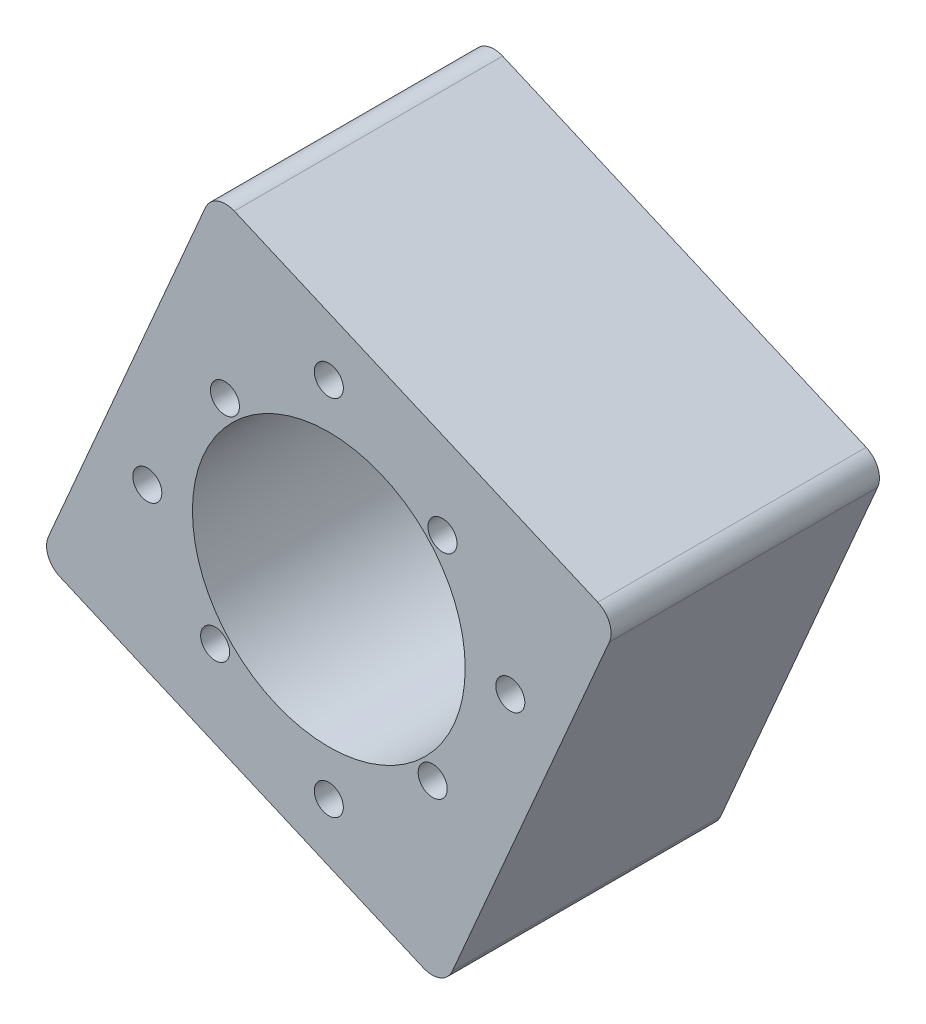
SolidWorks part; units mm, degrees
ref_plane "Plan de face" through (0, 0, 0) normal (0, 0, 1) x (1, 0, 0)
ref_plane "Plan de dessus" through (0, 0, 0) normal (0, 1, 0) x (1, 0, 0)
ref_plane "Plan de droite" through (0, 0, 0) normal (1, 0, 0) x (0, 0, -1)
sketch "Esquisse1" plane through (0, 0, 0) normal (0, 0, 1) x (1, 0, 0)
  circle A0 centre (0, 0) radius 50
  dimension "D1" = 100
extrude "Boss.-Extru.1" add sketch "Esquisse1" along normal blind 61
sketch "Esquisse2" plane through (0, 0, 0) normal (0, 0, -1) x (-1, 0, 0)
  circle A0 centre (0, 0) radius 31
  dimension "D1" = 62
extrude "Enlèv. mat.-Extru.1" cut sketch "Esquisse2" against normal blind 72
sketch "Esquisse8" plane through (0, 0, 0) normal (0, 0, -1) x (-1, 0, 0)
  circle A2 centre (0, 0) radius 41.25
  circle A3 centre (0, 0) radius 41.25 construction
  dimension "D1" = 8.75
hole_wizard "Chambrage pour vis à tête ronde bombée M61" positions "Esquisse12" profile "Esquisse11" counterbore size "M6" standard "Ansi Metric" end condition through all
sketch "Esquisse12" plane through (0, 0, 0) normal (0, 0, -1) x (-1, 0, 0)
  circle A0 centre (0, 0) radius 41.25 construction
  point P0 (41.25, 0)
  point P4 (0, 41.25)
  point P6 (-41.25, 0)
  point P8 (0, -41.25)
sketch "Esquisse11" plane through (-41.25, 0, 0) normal (1, 0, 0) x (0, 1, 0)
  line L0 (0, 0) -> (0, 61)
  line L1 (0, 61) -> (3.3, 61)
  line L3 (3.3, 61) -> (3.3, 4.6)
  line L4 (3.3, 4.6) -> (6.5, 4.6)
  line L5 (6.5, 4.6) -> (6.5, 0)
  line L7 (6.5, 0) -> (0, 0)
  line L11 (0, -6.35) -> (0, 107.95) construction
  dimension "Diamètre du perçage jusqu'au prochain" = 6.6
  dimension "Profondeur du perçage jusqu'au prochain" = 61
  dimension "Diamètre du chambrage" = 13
  dimension "Profondeur du chambrage" = 4.6
hole_wizard "Dégagement M61" positions "Esquisse18" profile "Esquisse19" hole size "M6" standard "JIS"
sketch "Esquisse18" plane through (0, 0, 61) normal (0, 0, 1) x (1, 0, 0)
  point P0 (-23.6086, 25.8386)
  point P2 (-25.8386, -23.6086)
  point P4 (23.6086, -25.8386)
  point P6 (25.8386, 23.6086)
sketch "Esquisse19" plane through (-23.6086, 25.8386, 61) normal (1, 0, 0) x (0, -1, 0)
  line L0 (0, 0) -> (0, 6.9053)
  line L1 (0, 6.9053) -> (3.3, 5)
  line L2 (3.3, 5) -> (3.3, 0)
  line L5 (3.3, 0) -> (0, 0)
  line L10 (0, 6.9053) -> (-3.3, 5) construction
  line L11 (0, -6.35) -> (0, 107.95) construction
  dimension "Diamètre du perçage" = 6.6
  dimension "Profondeur du perçage" = 5
  dimension "Angle de pointe" = 120
sketch "Esquisse20" plane through (0, 0, 0) normal (0, 0, -1) x (-1, 0, 0)
  line L0 (77.9159, 134.8474) -> (140.3944, -9.797) construction
  line L1 (28.0569, 61.1376) -> (63.7451, -21.4841)
  line L2 (21.4841, 63.7451) -> (-61.1376, 28.0569)
  line L3 (61.1376, -28.0569) -> (-21.4841, -63.7451)
  line L4 (-63.7451, 21.4841) -> (-28.0569, -61.1376)
  line L5 (-30.9182, 204.5053) -> (-132.5759, 160.5946) construction
  circle A2 centre (0, 0) radius 50 construction
  arc A3 (-63.7451, 21.4841) -> (-61.1376, 28.0569) centre (-59.155, 23.4668) cw
  arc A4 (-28.0569, -61.1376) -> (-21.4841, -63.7451) centre (-23.4668, -59.155) ccw
  arc A5 (61.1376, -28.0569) -> (63.7451, -21.4841) centre (59.155, -23.4668) ccw
  arc A6 (21.4841, 63.7451) -> (28.0569, 61.1376) centre (23.4668, 59.155) cw
  dimension "D1" = 5
extrude "Boss.-Extru.2" add sketch "Esquisse20" against normal offset from surface (61 mm away) 61
sketch "Esquisse23" plane through (0, 0, 0) normal (0, 0, -1) x (-1, 0, 0)
  circle A0 centre (0, 0) radius 31
  circle A1 centre (0, 0) radius 25
  dimension "D1" = 50
extrude "Boss.-Extru.3" add sketch "Esquisse23" against normal blind 7
sketch "Esquisse24" plane through (0, 0, 0) normal (0, 0, -1) x (-1, 0, 0)
  circle A0 centre (0, 0) radius 31
  dimension "D1" = 62
extrude "Enlèv. mat.-Extru.2" cut sketch "Esquisse24" against normal blind 3
